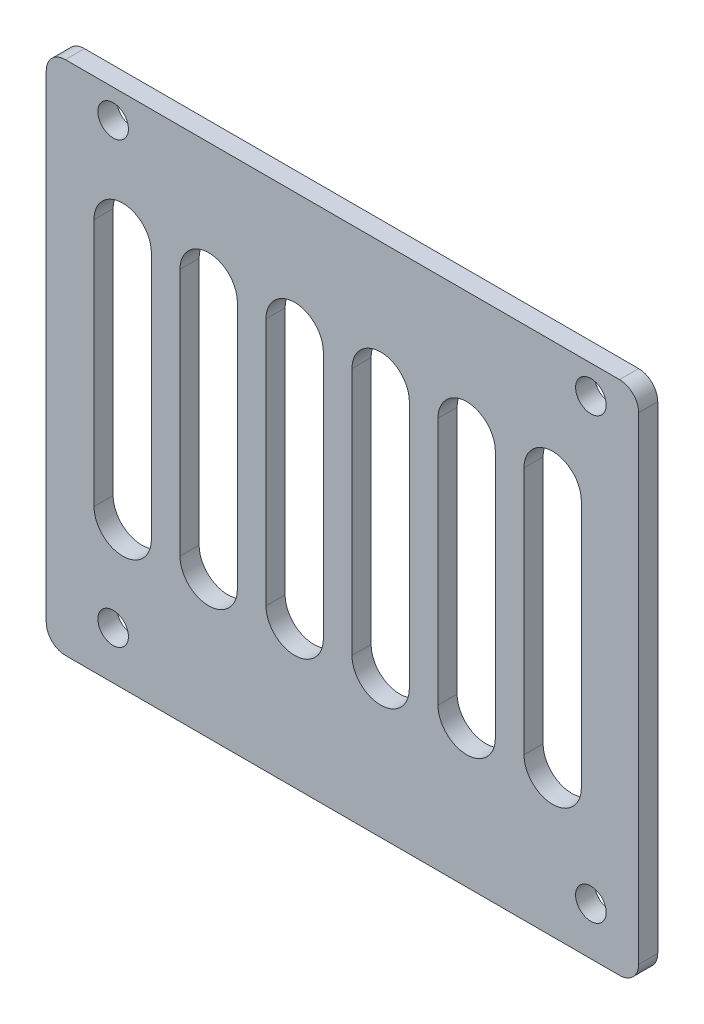
SolidWorks part; units mm, degrees
material "Thornel Mat VMA"
ref_plane "前视基准面" through (0, 0, 0) normal (0, 0, 1) x (1, 0, 0)
ref_plane "上视基准面" through (0, 0, 0) normal (0, 1, 0) x (1, 0, 0)
ref_plane "右视基准面" through (0, 0, 0) normal (1, 0, 0) x (0, 0, -1)
sketch "草图1" plane through (0, 0, 0) normal (0, 0, 1) x (1, 0, 0)
  line L0 (0, -28) -> (58, -28)
  line L1 (60, -26) -> (60, 24)
  line L2 (58, 26) -> (0, 26)
  line L3 (-2, 24) -> (-2, -26)
  line L4 (11, 26) -> (26, 26) construction
  line L5 (0, 0) -> (62.7863, 0) construction
  line L6 (6, 13) -> (6, -13) construction
  line L7 (9, 13) -> (9, -13)
  line L8 (3, 13) -> (3, -13)
  line L9 (15, 13) -> (15, -13) construction
  line L10 (18, 13) -> (18, -13)
  line L11 (12, 13) -> (12, -13)
  line L12 (24, 13) -> (24, -13) construction
  line L13 (27, 13) -> (27, -13)
  line L14 (21, 13) -> (21, -13)
  line L15 (33, 13) -> (33, -13) construction
  line L16 (36, 13) -> (36, -13)
  line L17 (30, 13) -> (30, -13)
  line L18 (42, 13) -> (42, -13) construction
  line L19 (45, 13) -> (45, -13)
  line L20 (39, 13) -> (39, -13)
  line L21 (51, 13) -> (51, -13) construction
  line L22 (54, 13) -> (54, -13)
  line L23 (48, 13) -> (48, -13)
  circle A0 centre (5, 23) radius 1.6
  circle A1 centre (55, 23) radius 1.6
  circle A2 centre (55, -23) radius 1.6
  circle A3 centre (5, -23) radius 1.6
  arc A4 (60, 24) -> (58, 26) centre (58, 24) ccw
  arc A5 (58, -28) -> (60, -26) centre (58, -26) ccw
  arc A6 (0, -28) -> (-2, -26) centre (0, -26) cw
  arc A7 (0, 26) -> (-2, 24) centre (0, 24) ccw
  arc A8 (9, 13) -> (3, 13) centre (6, 13) ccw
  arc A9 (3, -13) -> (9, -13) centre (6, -13) ccw
  arc A10 (18, 13) -> (12, 13) centre (15, 13) ccw
  arc A11 (12, -13) -> (18, -13) centre (15, -13) ccw
  arc A12 (27, 13) -> (21, 13) centre (24, 13) ccw
  arc A13 (21, -13) -> (27, -13) centre (24, -13) ccw
  arc A14 (36, 13) -> (30, 13) centre (33, 13) ccw
  arc A15 (30, -13) -> (36, -13) centre (33, -13) ccw
  arc A16 (45, 13) -> (39, 13) centre (42, 13) ccw
  arc A17 (39, -13) -> (45, -13) centre (42, -13) ccw
  arc A18 (54, 13) -> (48, 13) centre (51, 13) ccw
  arc A19 (48, -13) -> (54, -13) centre (51, -13) ccw
  point P22 (60, 28)
  point P25 (60, -28)
  point P28 (-2, -28)
  point P31 (-2, 28)
  point P39 (6, 0)
  point P48 (15, 0)
  point P55 (24, 0)
  point P62 (33, 0)
  point P69 (42, 0)
  point P76 (51, 0)
  dimension "D1" = 3.2
  dimension "D2" = 3.2
  dimension "D3" = 3.2
  dimension "D4" = 3.2
  dimension "D5" = 2
  dimension "D6" = 8
  dimension "D7" = 6
  dimension "D8" = 26
  dimension "D9" = 6
extrude "凸台-拉伸1" add sketch "草图1" along normal blind 2
